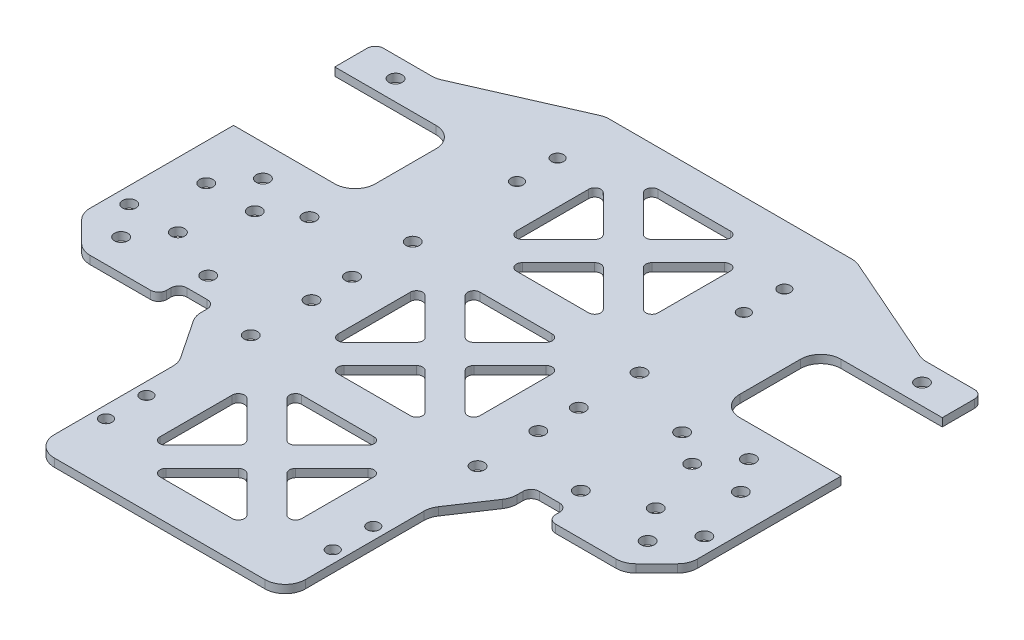
SolidWorks part; units mm, degrees
ref_plane "前视基准面" through (0, 0, 0) normal (0, 0, 1) x (1, 0, 0)
ref_plane "上视基准面" through (0, 0, 0) normal (0, 1, 0) x (1, 0, 0)
ref_plane "右视基准面" through (0, 0, 0) normal (1, 0, 0) x (0, 0, -1)
sketch "草图1" plane through (0, 0, 0) normal (0, 1, 0) x (1, 0, 0)
  line L1 (-75, -70.5) -> (75, -70.5)
  line L2 (-75, -70.5) -> (-75, 70.5)
  line L3 (-75, 70.5) -> (75, 70.5)
  line L4 (75, -70.5) -> (75, 70.5)
  line L5 (-75, -70.5) -> (75, 70.5) construction
  line L6 (-75, 70.5) -> (75, -70.5) construction
  point P0 (0, 0)
  dimension "D1" = 141
  dimension "D2" = 150
extrude "凸台-拉伸1" add sketch "草图1" along normal blind 2
sketch "草图2" plane through (0, 2, 0) normal (0, 1, 0) x (1, 0, 0)
  line L0 (-60, -11) -> (-65, -11) construction
  line L1 (-60, -11) -> (60, -11) construction
  line L2 (-60, -11) -> (-60, 11) construction
  line L3 (-60, 11) -> (60, 11) construction
  line L4 (60, -11) -> (60, 11) construction
  line L5 (-60, -11) -> (60, 11) construction
  line L6 (-60, 11) -> (60, -11) construction
  line L11 (-75, 70.5) -> (-75, -70.5) construction
  line L12 (-66, 7) -> (-54, 7) construction
  line L13 (-71, -15) -> (-59, -15) construction
  line L14 (-66, 7) -> (-66, 15) construction
  line L15 (-66, 15) -> (-54, 15) construction
  line L16 (-54, 7) -> (-54, 15) construction
  line L17 (-66, 7) -> (-54, 15) construction
  line L18 (-66, 15) -> (-54, 7) construction
  line L19 (-71, -15) -> (-71, -7) construction
  line L20 (-71, -7) -> (-59, -7) construction
  line L21 (-59, -15) -> (-59, -7) construction
  line L22 (-71, -15) -> (-59, -7) construction
  line L23 (-71, -7) -> (-59, -15) construction
  circle A4 centre (-60, 15) radius 1.65
  circle A5 centre (-66, 7) radius 1.65
  circle A6 centre (-54, 7) radius 1.65
  circle A7 centre (-71, -7) radius 1.65
  circle A8 centre (-59, -7) radius 1.65
  circle A9 centre (-65, -15) radius 1.65
  point P0 (0, 0)
  point P14 (-60, 0)
  dimension "D5" = 3.3
  dimension "D1" = 12
  dimension "D2" = 8
  dimension "D3" = 15
  dimension "D4" = 15
  dimension "D6" = 5
  dimension "D7" = 8
  dimension "D8" = 12
extrude "切除-拉伸1" cut sketch "草图2" against normal up to next
sketch "草图9" plane through (0, 2, 0) normal (0, 1, 0) x (1, 0, 0)
  line L0 (0, 22.75) -> (0, -22.75) construction
  line L1 (-75, -70.5) -> (-31, -70.5)
  line L2 (-75, -70.5) -> (-75, -22.75)
  line L3 (-75, -22.75) -> (-31, -22.75)
  line L4 (-31, -70.5) -> (-31, -22.75)
  line L5 (75, -70.5) -> (31, -70.5)
  line L6 (75, -70.5) -> (75, -22.75)
  line L7 (75, -22.75) -> (31, -22.75)
  line L8 (31, -70.5) -> (31, -22.75)
  point P14 (0, 0)
  dimension "D1" = 45.5
  dimension "D2" = 62
extrude "切除-拉伸5" cut sketch "草图9" against normal up to next
sketch "草图4" plane through (0, 2, 0) normal (0, 1, 0) x (1, 0, 0)
  line L1 (-31, -22.75) -> (-75, -22.75) construction
  line L2 (-75, 70.5) -> (-75, -22.75) construction
  line L3 (-39, -22.75) -> (-48, -22.75)
  line L4 (-39, -22.75) -> (-39, -17.75)
  line L5 (-39, -17.75) -> (-48, -17.75)
  line L6 (-48, -22.75) -> (-48, -17.75)
  dimension "D1" = 27
  dimension "D2" = 9
  dimension "D3" = 5
extrude "切除-拉伸2" cut sketch "草图4" against normal up to next
sketch "草图10" plane through (0, 2, 0) normal (0, 1, 0) x (1, 0, 0)
  line L0 (-75, 70.5) -> (-31, 70.5)
  line L1 (75, 70.5) -> (-75, 70.5) construction
  line L2 (-31, 70.5) -> (-60, 57.75)
  line L3 (-60, 57.75) -> (-75, 57.75)
  line L4 (-75, 70.5) -> (-75, -22.75) construction
  line L5 (-75, 57.75) -> (-75, 70.5)
  line L6 (-31, -70.5) -> (-31, 70.5) construction
  dimension "D1" = 15
  dimension "D2" = 12.75
extrude "切除-拉伸6" cut sketch "草图10" against normal up to next
mirror "镜向1" about plane through (0, 0, 0) normal (1, 0, 0) of "切除-拉伸6", "切除-拉伸1", "切除-拉伸2"
chamfer "倒角1" distance 8 angle 45 2 edges at (75, 1, 22.75) (-75, 1, 22.75)
sketch "草图5" plane through (0, 2, 0) normal (0, 1, 0) x (1, 0, 0)
  line L1 (-28, 5) -> (28, 5) construction
  line L2 (-28, 5) -> (-28, -5) construction
  line L3 (-28, -5) -> (28, -5) construction
  line L4 (28, 5) -> (28, -5) construction
  line L5 (-28, 5) -> (28, -5) construction
  line L6 (-28, -5) -> (28, 5) construction
  circle A0 centre (-28, 5) radius 1.65
  circle A1 centre (-28, -5) radius 1.65
  circle A2 centre (28, -5) radius 1.65
  circle A3 centre (28, 5) radius 1.65
  point P0 (0, 0)
  dimension "D3" = 3.3
  dimension "D1" = 56
  dimension "D2" = 10
extrude "切除-拉伸3" cut sketch "草图5" against normal up to next
sketch "草图7" plane through (0, 0, 0) normal (0, 1, 0) x (1, 0, 0)
  line L7 (-39, -22.75) -> (-31, -34.75)
  line L11 (-31, -70.5) -> (-31, -22.75) construction
  line L14 (-31, -34.75) -> (-31, -22.75)
  line L15 (-31, -22.75) -> (-39, -22.75)
  line L17 (31, -22.75) -> (39, -22.75)
  line L18 (39, -22.75) -> (31, -34.75)
  line L20 (31, -22.75) -> (31, -70.5) construction
  line L21 (31, -34.75) -> (31, -22.75)
  line L22 (-31, -34.75) -> (31, -34.75) construction
  dimension "D1" = 12
extrude "凸台-拉伸4" add sketch "草图7" along normal up to surface (2 mm away) up to face at (28, 2, -3.35)
sketch "草图8" plane through (0, 2, 0) normal (0, 1, 0) x (1, 0, 0)
  line L0 (0, 0) -> (0, -50.75) construction
  line L3 (-28, -55.75) -> (28, -55.75) construction
  line L4 (-28, -55.75) -> (-28, -45.75) construction
  line L5 (-28, -45.75) -> (28, -45.75) construction
  line L6 (28, -55.75) -> (28, -45.75) construction
  line L7 (-28, -55.75) -> (28, -45.75) construction
  line L8 (-28, -45.75) -> (28, -55.75) construction
  circle A0 centre (-28, -45.75) radius 1.5
  circle A1 centre (-28, -55.75) radius 1.5
  circle A2 centre (28, -45.75) radius 1.5
  circle A3 centre (28, -55.75) radius 1.5
  dimension "D4" = 3
  dimension "D1" = 10
  dimension "D2" = 56
  dimension "D3" = 50.75
extrude "切除-拉伸4" cut sketch "草图8" against normal up to next
sketch "草图11" plane through (0, 2, 0) normal (0, 1, 0) x (1, 0, 0)
  line L0 (-75, 57.75) -> (-75, -14.75) construction
  line L1 (-75, 47.75) -> (-45, 47.75)
  line L2 (-75, 47.75) -> (-75, 22.75)
  line L3 (-75, 22.75) -> (-45, 22.75)
  line L4 (-45, 47.75) -> (-45, 22.75)
  line L5 (-75, 57.75) -> (-60, 57.75) construction
  line L6 (0, 0) -> (0, 70.5) construction
  line L7 (31, 70.5) -> (-31, 70.5) construction
  line L8 (75, 22.75) -> (45, 22.75)
  line L9 (45, 47.75) -> (45, 22.75)
  line L10 (75, 47.75) -> (45, 47.75)
  line L11 (75, 47.75) -> (75, 22.75)
  dimension "D1" = 10
  dimension "D2" = 30
  dimension "D3" = 25
extrude "切除-拉伸7" cut sketch "草图11" against normal up to next
mirror "镜向2" about plane through (0, 0, 0) normal (0, 0, 1) of "切除-拉伸4"
fillet "圆角5" radius 5 18 edges at (75, 1, 14.75) (67, 1, 22.75) (-67, 1, 22.75) (-75, 1, 14.75) (45, 1, -22.75) (45, 1, -47.75) (-45, 1, -22.75) (-45, 1, -47.75) (31, 1, 34.75) (-31, 1, 34.75) (39, 1, 22.75) (-39, 1, 22.75) (60, 1, -57.75) (31, 1, -70.5) (-31, 1, -70.5) (-60, 1, -57.75) (31, 1, 70.5) (-31, 1, 70.5)
fillet "圆角6" radius 2 6 edges at (48, 1, 22.75) (48, 1, 17.75) (39, 1, 17.75) (-39, 1, 17.75) (-48, 1, 22.75) (-48, 1, 17.75)
sketch "草图12" plane through (0, 2, 0) normal (0, 1, 0) x (1, 0, 0)
  line L0 (-75, 52.75) -> (-65, 52.75) construction
  line L1 (-75, 57.75) -> (-75, 47.75) construction
  line L2 (0, 0) -> (0, 70.5) construction
  line L3 (29.9494, 70.5) -> (-29.9494, 70.5) construction
  circle A0 centre (-65, 52.75) radius 1.65
  circle A1 centre (65, 52.75) radius 1.65
  dimension "D1" = 3.3
  dimension "D2" = 10
extrude "切除-拉伸8" cut sketch "草图12" against normal up to next
fillet "圆角7" radius 2 2 edges at (75, 1, -57.75) (-75, 1, -57.75)
sketch "草图13" plane through (0, 2, 0) normal (0, 1, 0) x (1, 0, 0)
  line L1 (46, 12.5) -> (-46, 12.5) construction
  line L2 (46, 12.5) -> (46, -12.5) construction
  line L3 (46, -12.5) -> (-46, -12.5) construction
  line L4 (-46, 12.5) -> (-46, -12.5) construction
  line L5 (46, 12.5) -> (-46, -12.5) construction
  line L6 (46, -12.5) -> (-46, 12.5) construction
  circle A0 centre (-46, 12.5) radius 1.65
  circle A1 centre (-46, -12.5) radius 1.65
  circle A2 centre (46, 12.5) radius 1.65
  circle A3 centre (46, -12.5) radius 1.65
  point P0 (0, 0)
  dimension "D3" = 3.3
  dimension "D1" = 92
  dimension "D2" = 25
extrude "切除-拉伸9" cut sketch "草图13" against normal up to next
sketch "草图14" plane through (0, 2, 0) normal (0, 1, 0) x (1, 0, 0)
  line L1 (-28, -20) -> (28, -20) construction
  line L2 (-28, -20) -> (-28, 20) construction
  line L3 (-28, 20) -> (28, 20) construction
  line L4 (28, -20) -> (28, 20) construction
  line L5 (-28, -20) -> (28, 20) construction
  line L6 (-28, 20) -> (28, -20) construction
  circle A6 centre (-28, 20) radius 1.65
  circle A7 centre (28, 20) radius 1.65
  circle A8 centre (-28, -20) radius 1.65
  circle A9 centre (28, -20) radius 1.65
  point P0 (0, 0)
  point P8 (-28, 5)
  dimension "D2" = 3.3
  dimension "D1" = 40
extrude "切除-拉伸11" cut sketch "草图14" against normal up to next
sketch "草图15" plane through (0, 2, 0) normal (0, 1, 0) x (1, 0, 0)
  line L0 (0, 4.9497) -> (0, -4.9497) construction
  line L15 (-17.5, -12.5503) -> (17.5, -12.5503) construction
  line L16 (-17.5, -12.5503) -> (-17.5, 12.5503)
  line L17 (-17.5, 12.5503) -> (17.5, 12.5503) construction
  line L18 (17.5, -12.5503) -> (17.5, 12.5503)
  line L19 (-17.5, -12.5503) -> (17.5, 12.5503) construction
  line L20 (-17.5, 12.5503) -> (17.5, -12.5503) construction
  line L21 (-12.5503, 17.5) -> (12.5503, 17.5)
  line L22 (-12.5503, 17.5) -> (-12.5503, -17.5) construction
  line L23 (-12.5503, -17.5) -> (12.5503, -17.5)
  line L24 (12.5503, 17.5) -> (12.5503, -17.5) construction
  line L25 (-12.5503, 17.5) -> (12.5503, -17.5) construction
  line L26 (-12.5503, -17.5) -> (12.5503, 17.5) construction
  line L27 (-4.9497, 0) -> (4.9497, 0) construction
  line L28 (-12.5503, 17.5) -> (0, 4.9497)
  line L29 (0, 4.9497) -> (12.5503, 17.5)
  line L30 (17.5, 12.5503) -> (4.9497, 0)
  line L31 (4.9497, 0) -> (17.5, -12.5503)
  line L32 (12.5503, -17.5) -> (0, -4.9497)
  line L33 (0, -4.9497) -> (-12.5503, -17.5)
  line L34 (-17.5, -12.5503) -> (-4.9497, 0)
  line L35 (-4.9497, 0) -> (-17.5, 12.5503)
  line L36 (-17.5, -12.5503) -> (-12.5503, -17.5) construction
  point P0 (0, 0)
  point P5 (0, 0)
  point P14 (0, 0)
  point P17 (0, 0)
  dimension "D1" = 35
  dimension "D2" = 35
  dimension "D3" = 7
  dimension "D4" = 45
extrude "切除-拉伸12" cut sketch "草图15" against normal up to next
fillet "圆角8" radius 1.5 12 edges at (12.5503, 1, 17.5) (-12.5503, 1, 17.5) (0, 1, 4.9497) (17.5, 1, 12.5503) (4.9497, 1, 0) (0, 1, -4.9497) (17.5, 1, -12.5503) (12.5503, 1, -17.5) (-12.5503, 1, -17.5) (-4.9497, 1, 0) (-17.5, 1, 12.5503) (-17.5, 1, -12.5503)
pattern_linear "阵列(线性)1" count 2 spacing 44 along (0, 0, -1) of "切除-拉伸12", "圆角8"
pattern_linear "阵列(线性)2" count 2 spacing 44 along (0, 0, 1) of "切除-拉伸12", "圆角8"
